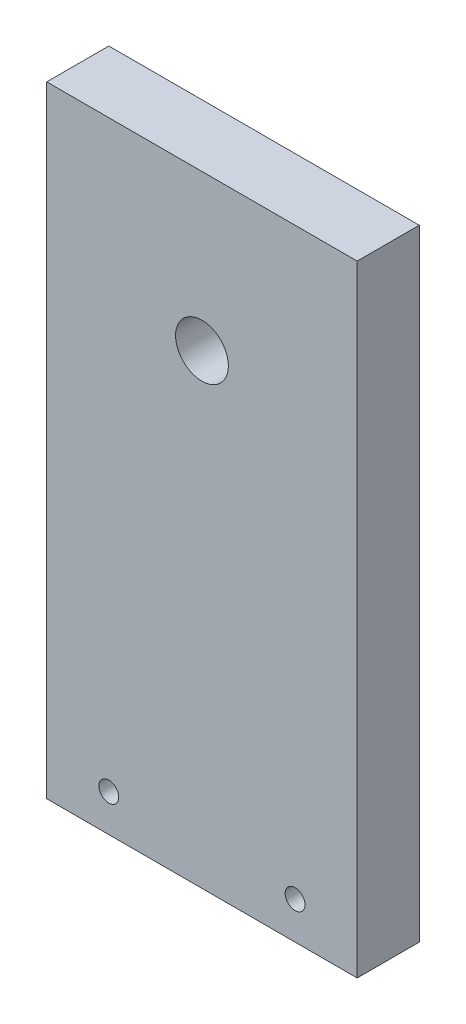
SolidWorks part; units mm, degrees
ref_plane "Front Plane" through (0, 0, 0) normal (0, 0, 1) x (1, 0, 0)
ref_plane "Top Plane" through (0, 0, 0) normal (0, 1, 0) x (1, 0, 0)
ref_plane "Right Plane" through (0, 0, 0) normal (1, 0, 0) x (0, 0, -1)
sketch "Sketch1" plane through (0, 0, 0) normal (0, 0, 1) x (1, 0, 0)
  line L1 (-25, 0) -> (25, 0)
  line L2 (-25, 0) -> (-25, 100)
  line L3 (-25, 100) -> (25, 100)
  line L4 (25, 0) -> (25, 100)
extrude "Boss-Extrude1" add sketch "Sketch1" along normal blind 10
sketch "Sketch2" plane through (0, 0, 0) normal (0, 0, 1) x (1, 0, 0)
  circle A0 centre (0, 75) radius 4.25
  circle A1 centre (15, 6) radius 1.6
  circle A2 centre (-15, 6) radius 1.6
extrude "Cut-Extrude2" cut sketch "Sketch2" along normal blind 11
